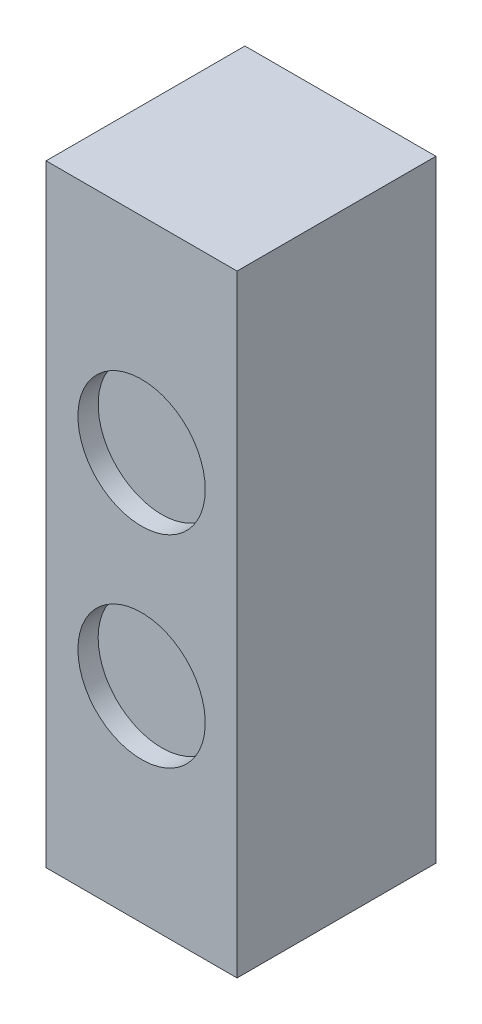
SolidWorks part; units mm, degrees
ref_plane "Front Plane" through (0, 0, 0) normal (0, 0, 1) x (1, 0, 0)
ref_plane "Top Plane" through (0, 0, 0) normal (0, 1, 0) x (1, 0, 0)
ref_plane "Right Plane" through (0, 0, 0) normal (1, 0, 0) x (0, 0, -1)
sketch "Sketch2" plane through (0, 0, 0) normal (0, 0, 1) x (1, 0, 0)
  line L1 (0, 0) -> (24.003, 0)
  line L2 (0, 0) -> (0, 76.962)
  line L3 (0, 76.962) -> (24.003, 76.962)
  line L4 (24.003, 0) -> (24.003, 76.962)
  dimension "D1" = 76.962
  dimension "D2" = 24.003
extrude "Boss-Extrude1" add sketch "Sketch2" along normal blind 24.9936
sketch "Sketch3" plane through (0, 0, 24.9936) normal (0, 0, 1) x (1, 0, 0)
  line L0 (12.0015, 76.962) -> (12.0015, 0) construction
  line L1 (24.003, 76.962) -> (0, 76.962) construction
  line L2 (0, 0) -> (24.003, 0) construction
  line L3 (0, 38.481) -> (24.003, 38.481) construction
  line L4 (0, 76.962) -> (0, 0) construction
  line L5 (24.003, 0) -> (24.003, 76.962) construction
  circle A0 centre (12.0015, 51.181) radius 8.001
  circle A2 centre (12.0015, 25.781) radius 8.001
  point P16 (0, 0)
  dimension "D1" = 16.002
  dimension "D2" = 12.7
extrude "Cut-Extrude1" cut sketch "Sketch3" against normal blind 2.54
